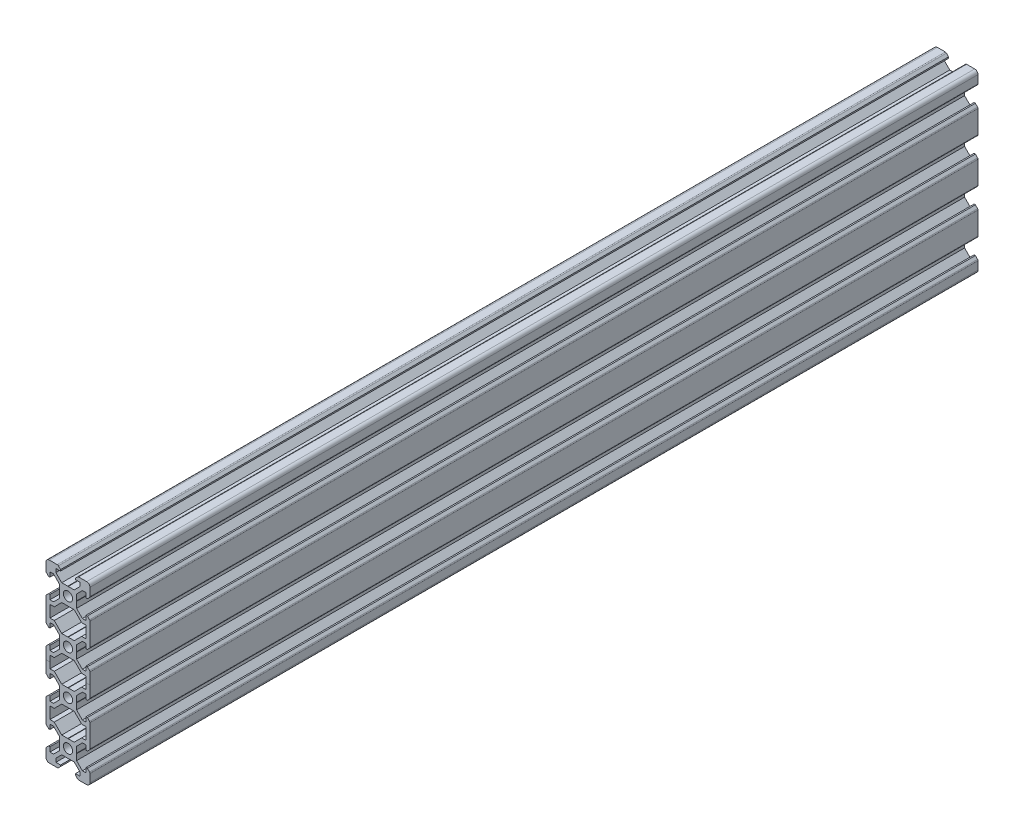
SolidWorks part; units mm, degrees
material "6063-T5"
ref_plane "Front" through (0, 0, 0) normal (0, 0, 1) x (1, 0, 0)
ref_plane "Top" through (0, 0, 0) normal (0, 1, 0) x (1, 0, 0)
ref_plane "Right" through (0, 0, 0) normal (1, 0, 0) x (0, 0, -1)
sketch "Sketch1" plane through (0, 0, 0) normal (0, 0, 1) x (1, 0, 0)
  line L0 (-8.5, 10) -> (-10, 8.5) construction
  line L1 (-8.5, 10) -> (-4.8628, 10)
  line L2 (-10, 8.5) -> (-10, 4.8628)
  line L3 (25.9287, -20) -> (-28.3599, -20) construction
  line L4 (10, 8.5) -> (10, 4.8628)
  line L5 (-10, 10) -> (10, -10) construction
  line L6 (-10, -10) -> (10, 10) construction
  line L7 (8.2, -5.5) -> (8.2, -3.3865)
  line L8 (-8.2, -5.5) -> (-8.2, -3.3865)
  line L9 (-5.5, 8.2) -> (-3.3865, 8.2)
  line L10 (-8.2, -12.7) -> (-8.2, -7.3)
  line L11 (-3.9005, 2.8395) -> (-6.561, 5.5)
  line L12 (-6.561, 5.5) -> (-8.2, 5.5)
  line L13 (-2.8395, -3.9005) -> (-0.1, -3.9005)
  line L14 (-3.9005, -2.8395) -> (-3.9005, -0.1)
  line L15 (-2.8395, 3.9005) -> (-0.1, 3.9005)
  line L16 (3.9005, -2.8395) -> (3.9005, -0.1)
  line L17 (-8.2, 3.3865) -> (-8.81, 3.3865)
  line L18 (-8.81, 3.3865) -> (-9.7976, 4.3741)
  line L19 (8.5, 10) -> (10, 8.5) construction
  line L20 (-2.8395, 3.9005) -> (-5.5, 6.561)
  line L21 (-5.5, 6.561) -> (-5.5, 8.2)
  line L22 (-3.3865, 8.2) -> (-3.3865, 8.81)
  line L23 (-3.3865, 8.81) -> (-4.3741, 9.7976)
  line L24 (0, 24.069) -> (0, -33.8154) construction
  line L25 (3.3865, 8.81) -> (4.3741, 9.7976)
  line L26 (3.3865, 8.2) -> (3.3865, 8.81)
  line L27 (5.5, 6.561) -> (5.5, 8.2)
  line L28 (2.8395, 3.9005) -> (5.5, 6.561)
  line L29 (3.3865, 8.2) -> (5.5, 8.2)
  line L30 (4.8628, 10) -> (8.5, 10)
  line L31 (-0.1, 3.9005) -> (0, 3.8005)
  line L32 (0.1, 3.9005) -> (0, 3.8005)
  line L33 (0.1, 3.9005) -> (2.8395, 3.9005)
  line L34 (25.9287, 0) -> (-28.3459, 0) construction
  line L35 (-0.1, -3.9005) -> (0, -3.8005)
  line L36 (0.1, -3.9005) -> (0, -3.8005)
  line L37 (0.1, -3.9005) -> (2.8395, -3.9005)
  line L38 (-3.9005, 0.1) -> (-3.8005, 0)
  line L39 (-3.8005, 0) -> (-3.9005, -0.1)
  line L40 (-3.9005, 0.1) -> (-3.9005, 2.8395)
  line L41 (3.9005, 0.1) -> (3.8005, 0)
  line L42 (3.8005, 0) -> (3.9005, -0.1)
  line L43 (3.9005, 0.1) -> (3.9005, 2.8395)
  line L44 (8.81, 3.3865) -> (9.7976, 4.3741)
  line L45 (8.2, 3.3865) -> (8.81, 3.3865)
  line L46 (6.561, 5.5) -> (8.2, 5.5)
  line L47 (3.9005, 2.8395) -> (6.561, 5.5)
  line L48 (2.8395, -3.9005) -> (5.5, -6.561)
  line L49 (3.9005, -2.8395) -> (6.561, -5.5)
  line L50 (-2.8395, -3.9005) -> (-5.5, -6.561)
  line L51 (-3.9005, -2.8395) -> (-6.561, -5.5)
  line L52 (6.561, -5.5) -> (8.2, -5.5)
  line L53 (-6.561, -5.5) -> (-8.2, -5.5)
  line L54 (-8.81, -3.3865) -> (-9.7976, -4.3741)
  line L55 (-8.2, -3.3865) -> (-8.81, -3.3865)
  line L56 (8.81, -3.3865) -> (9.7976, -4.3741)
  line L57 (8.2, -3.3865) -> (8.81, -3.3865)
  line L58 (8.2, 3.3865) -> (8.2, 5.5)
  line L59 (10, -4.8628) -> (10, -15.1372)
  line L60 (-8.2, 3.3865) -> (-8.2, 5.5)
  line L61 (-10, -4.8628) -> (-10, -15.1372)
  line L62 (-28.3459, -10) -> (-10, -10) construction
  line L63 (-3.9005, -20.1) -> (-3.9005, -22.8395)
  line L64 (-3.9005, -20.1) -> (-3.8005, -20)
  line L65 (-3.8005, -20) -> (-3.9005, -19.9)
  line L66 (3.9005, -20.1) -> (3.9005, -22.8395)
  line L67 (3.9005, -20.1) -> (3.8005, -20)
  line L68 (3.8005, -20) -> (3.9005, -19.9)
  line L69 (6.561, -14.5) -> (8.2, -14.5)
  line L70 (3.9005, -17.1605) -> (6.561, -14.5)
  line L71 (3.9005, -17.1605) -> (3.9005, -19.9)
  line L72 (-3.9005, -17.1605) -> (-3.9005, -19.9)
  line L73 (-3.9005, -17.1605) -> (-6.561, -14.5)
  line L74 (-6.561, -14.5) -> (-8.2, -14.5)
  line L75 (-8.2, -16.6135) -> (-8.81, -16.6135)
  line L76 (-8.81, -16.6135) -> (-9.7976, -15.6259)
  line L77 (8.2, -16.6135) -> (8.81, -16.6135)
  line L78 (8.81, -16.6135) -> (9.7976, -15.6259)
  line L79 (-2.8395, -16.0995) -> (-5.5, -13.439)
  line L80 (-2.8395, -16.0995) -> (-0.1, -16.0995)
  line L81 (-0.1, -16.0995) -> (0, -16.1995)
  line L82 (0.1, -16.0995) -> (0, -16.1995)
  line L83 (0.1, -16.0995) -> (2.8395, -16.0995)
  line L84 (2.8395, -16.0995) -> (5.5, -13.439)
  line L85 (-8.2, -16.6135) -> (-8.2, -14.5)
  line L86 (8.2, -16.6135) -> (8.2, -14.5)
  line L87 (2.8395, -23.9005) -> (5.5, -26.561)
  line L88 (-2.8395, -23.9005) -> (-5.5, -26.561)
  line L89 (-0.1, -23.9005) -> (0, -23.8005)
  line L90 (0.1, -23.9005) -> (0, -23.8005)
  line L91 (0.1, -23.9005) -> (2.8395, -23.9005)
  line L92 (-2.8395, -23.9005) -> (-0.1, -23.9005)
  line L93 (-8.2, -23.3865) -> (-8.2, -25.5)
  line L94 (-8.2, -23.3865) -> (-8.81, -23.3865)
  line L95 (-8.81, -23.3865) -> (-9.7976, -24.3741)
  line L96 (8.2, -23.3865) -> (8.2, -25.5)
  line L97 (8.2, -23.3865) -> (8.81, -23.3865)
  line L98 (8.81, -23.3865) -> (9.7976, -24.3741)
  line L99 (8.2, -27.3) -> (8.2, -32.7)
  line L100 (10, -35.1372) -> (10, -24.8628)
  line L101 (-10, -35.1372) -> (-10, -24.8628)
  line L102 (-8.2, -27.3) -> (-8.2, -32.7)
  line L103 (3.9005, -22.8395) -> (6.561, -25.5)
  line L104 (-3.9005, -22.8395) -> (-6.561, -25.5)
  line L105 (6.239, -27.3) -> (8.2, -27.3)
  line L106 (-6.239, -27.3) -> (-8.2, -27.3)
  line L107 (-6.561, -25.5) -> (-8.2, -25.5)
  line L108 (6.561, -25.5) -> (8.2, -25.5)
  line L109 (5.5, -26.561) -> (6.239, -27.3)
  line L110 (-5.5, -26.561) -> (-6.239, -27.3)
  line L111 (8.2, -34.5) -> (8.2, -36.6135)
  line L112 (8.2, -36.6135) -> (8.81, -36.6135)
  line L113 (8.81, -36.6135) -> (9.7976, -35.6259)
  line L114 (-8.2, -34.5) -> (-8.2, -36.6135)
  line L115 (-6.239, -7.3) -> (-8.2, -7.3)
  line L116 (-5.5, -6.561) -> (-6.239, -7.3)
  line L117 (6.239, -7.3) -> (8.2, -7.3)
  line L118 (5.5, -6.561) -> (6.239, -7.3)
  line L119 (-6.239, -12.7) -> (-8.2, -12.7)
  line L120 (-5.5, -13.439) -> (-6.239, -12.7)
  line L121 (5.5, -13.439) -> (6.239, -12.7)
  line L122 (6.239, -12.7) -> (8.2, -12.7)
  line L123 (8.2, -12.7) -> (8.2, -7.3)
  line L124 (-8.2, -36.6135) -> (-8.81, -36.6135)
  line L125 (10, -10) -> (25.9287, -10) construction
  line L126 (-8.81, -36.6135) -> (-9.7976, -35.6259)
  line L127 (-0.1, -56.0995) -> (0, -56.1995)
  line L128 (-0.1, -36.0995) -> (0, -36.1995)
  line L129 (0.1, -36.0995) -> (0, -36.1995)
  line L130 (0.1, -36.0995) -> (2.8395, -36.0995)
  line L131 (-6.561, -34.5) -> (-8.2, -34.5)
  line L132 (6.561, -34.5) -> (8.2, -34.5)
  line L133 (6.239, -32.7) -> (8.2, -32.7)
  line L134 (-6.239, -32.7) -> (-8.2, -32.7)
  line L135 (-5.5, -33.439) -> (-6.239, -32.7)
  line L136 (5.5, -33.439) -> (6.239, -32.7)
  line L137 (-26.6965, -30) -> (27.5921, -30) construction
  line L138 (0.1, -56.0995) -> (0, -56.1995)
  line L139 (0.1, -56.0995) -> (2.8395, -56.0995)
  line L140 (-2.8395, -56.0995) -> (-0.1, -56.0995)
  line L141 (0, -60) -> (0, -71.7864) construction
  line L142 (-3.8005, -60) -> (-3.9005, -59.9)
  line L143 (-3.9005, -60.1) -> (-3.8005, -60)
  line L144 (10, -68.5) -> (10, -64.8628)
  line L145 (0.1, -63.9005) -> (0, -63.8005)
  line L146 (-0.1, -63.9005) -> (0, -63.8005)
  line L147 (-2.8395, -63.9005) -> (-0.1, -63.9005)
  line L148 (0.1, -63.9005) -> (2.8395, -63.9005)
  line L149 (3.9005, -60.1) -> (3.9005, -62.8395)
  line L150 (3.9005, -60.1) -> (3.8005, -60)
  line L151 (3.8005, -60) -> (3.9005, -59.9)
  line L152 (3.9005, -57.1605) -> (3.9005, -59.9)
  line L153 (4.8628, -70) -> (8.5, -70)
  line L154 (3.3865, -68.81) -> (4.3741, -69.7976)
  line L155 (3.3865, -68.2) -> (3.3865, -68.81)
  line L156 (3.3865, -68.2) -> (5.5, -68.2)
  line L157 (-0.1, -43.9005) -> (0, -43.8005)
  line L158 (0.1, -43.9005) -> (0, -43.8005)
  line L159 (-2.8395, -43.9005) -> (-0.1, -43.9005)
  line L160 (0.1, -43.9005) -> (2.8395, -43.9005)
  line L161 (3.9005, -40.1) -> (3.8005, -40)
  line L162 (3.8005, -40) -> (3.9005, -39.9)
  line L163 (3.9005, -37.1605) -> (3.9005, -39.9)
  line L164 (3.9005, -40.1) -> (3.9005, -42.8395)
  line L165 (-2.8395, -36.0995) -> (-0.1, -36.0995)
  line L166 (-2.8395, -43.9005) -> (-5.5, -46.561)
  line L167 (-3.9005, -37.1605) -> (-3.9005, -39.9)
  line L168 (-3.8005, -40) -> (-3.9005, -39.9)
  line L169 (-3.9005, -40.1) -> (-3.8005, -40)
  line L170 (-3.9005, -42.8395) -> (-6.561, -45.5)
  line L171 (2.8395, -43.9005) -> (5.5, -46.561)
  line L172 (3.9005, -42.8395) -> (6.561, -45.5)
  line L173 (3.9005, -37.1605) -> (6.561, -34.5)
  line L174 (2.8395, -36.0995) -> (5.5, -33.439)
  line L175 (-3.9005, -42.8395) -> (-3.9005, -40.1)
  line L176 (-6.561, -34.5) -> (-3.9005, -37.1605)
  line L177 (-5.5, -33.439) -> (-2.8395, -36.0995)
  line L178 (5.5, -66.561) -> (5.5, -68.2)
  line L179 (6.561, -65.5) -> (8.2, -65.5)
  line L180 (8.2, -63.3865) -> (8.2, -65.5)
  line L181 (8.81, -63.3865) -> (9.7976, -64.3741)
  line L182 (8.2, -63.3865) -> (8.81, -63.3865)
  line L183 (-8.2, -63.3865) -> (-8.81, -63.3865)
  line L184 (-8.81, -63.3865) -> (-9.7976, -64.3741)
  line L185 (-8.2, -63.3865) -> (-8.2, -65.5)
  line L186 (-6.561, -65.5) -> (-8.2, -65.5)
  line L187 (-5.5, -66.561) -> (-5.5, -68.2)
  line L188 (-5.5, -68.2) -> (-3.3865, -68.2)
  line L189 (-3.3865, -68.2) -> (-3.3865, -68.81)
  line L190 (-3.3865, -68.81) -> (-4.3741, -69.7976)
  line L191 (-10, -68.5) -> (-10, -64.8628)
  line L192 (-8.5, -70) -> (-4.8628, -70)
  line L193 (-8.2, -43.3865) -> (-8.81, -43.3865)
  line L194 (-8.81, -43.3865) -> (-9.7976, -44.3741)
  line L195 (-10, -55.1372) -> (-10, -44.8628)
  line L196 (-8.81, -56.6135) -> (-9.7976, -55.6259)
  line L197 (-8.2, -56.6135) -> (-8.81, -56.6135)
  line L198 (8.2, -56.6135) -> (8.81, -56.6135)
  line L199 (8.81, -56.6135) -> (9.7976, -55.6259)
  line L200 (8.2, -43.3865) -> (8.81, -43.3865)
  line L201 (8.81, -43.3865) -> (9.7976, -44.3741)
  line L202 (10, -55.1372) -> (10, -44.8628)
  line L203 (-8.2, -47.3) -> (-8.2, -52.7)
  line L204 (8.2, -47.3) -> (8.2, -52.7)
  line L205 (-6.239, -52.7) -> (-8.2, -52.7)
  line L206 (6.239, -52.7) -> (8.2, -52.7)
  line L207 (-6.561, -54.5) -> (-8.2, -54.5)
  line L208 (6.561, -54.5) -> (8.2, -54.5)
  line L209 (-3.9005, -60.1) -> (-3.9005, -62.8395)
  line L210 (-2.8395, -56.0995) -> (-5.5, -53.439)
  line L211 (3.9005, -57.1605) -> (6.561, -54.5)
  line L212 (2.8395, -56.0995) -> (5.5, -53.439)
  line L213 (5.5, -53.439) -> (6.239, -52.7)
  line L214 (-5.5, -53.439) -> (-6.239, -52.7)
  line L215 (-8.2, -43.3865) -> (-8.2, -45.5)
  line L216 (8.2, -43.3865) -> (8.2, -45.5)
  line L217 (-2.8395, -63.9005) -> (-5.5, -66.561)
  line L218 (-3.9005, -62.8395) -> (-6.561, -65.5)
  line L219 (2.8395, -63.9005) -> (5.5, -66.561)
  line L220 (3.9005, -62.8395) -> (6.561, -65.5)
  line L221 (-8.2, -54.5) -> (-8.2, -56.6135)
  line L222 (8.2, -54.5) -> (8.2, -56.6135)
  line L223 (6.239, -47.3) -> (8.2, -47.3)
  line L224 (-6.239, -47.3) -> (-8.2, -47.3)
  line L225 (-6.561, -45.5) -> (-8.2, -45.5)
  line L226 (-5.5, -46.561) -> (-6.239, -47.3)
  line L227 (6.561, -45.5) -> (8.2, -45.5)
  line L228 (5.5, -46.561) -> (6.239, -47.3)
  line L229 (-3.9005, -57.1605) -> (-3.9005, -59.9)
  line L230 (-3.9005, -57.1605) -> (-6.561, -54.5)
  circle A0 centre (0, 0) radius 2.1
  arc A1 (-8.5, 10) -> (-10, 8.5) centre (-8.5, 8.5) ccw
  arc A2 (10, 8.5) -> (8.5, 10) centre (8.5, 8.5) ccw
  arc A3 (-4.3741, 9.7976) -> (-4.8628, 10) centre (-4.8628, 9.3088) ccw
  arc A4 (4.8628, 10) -> (4.3741, 9.7976) centre (4.8628, 9.3088) ccw
  circle A5 centre (0, -20) radius 2.1
  arc A6 (9.7976, 4.3741) -> (10, 4.8628) centre (9.3088, 4.8628) ccw
  arc A7 (-10, 4.8628) -> (-9.7976, 4.3741) centre (-9.3088, 4.8628) ccw
  arc A8 (-10, -4.8628) -> (-9.7976, -4.3741) centre (-9.3088, -4.8628) cw
  arc A9 (9.7976, -4.3741) -> (10, -4.8628) centre (9.3088, -4.8628) cw
  arc A10 (-10, -15.1372) -> (-9.7976, -15.6259) centre (-9.3088, -15.1372) ccw
  arc A11 (9.7976, -15.6259) -> (10, -15.1372) centre (9.3088, -15.1372) ccw
  arc A12 (-10, -24.8628) -> (-9.7976, -24.3741) centre (-9.3088, -24.8628) cw
  arc A13 (9.7976, -24.3741) -> (10, -24.8628) centre (9.3088, -24.8628) cw
  arc A14 (9.7976, -35.6259) -> (10, -35.1372) centre (9.3088, -35.1372) ccw
  arc A15 (-10, -35.1372) -> (-9.7976, -35.6259) centre (-9.3088, -35.1372) ccw
  circle A16 centre (0, -40) radius 2.1
  circle A17 centre (0, -60) radius 2.1
  arc A18 (10, -68.5) -> (8.5, -70) centre (8.5, -68.5) cw
  arc A19 (4.8628, -70) -> (4.3741, -69.7976) centre (4.8628, -69.3088) cw
  arc A20 (9.7976, -64.3741) -> (10, -64.8628) centre (9.3088, -64.8628) cw
  arc A21 (-10, -64.8628) -> (-9.7976, -64.3741) centre (-9.3088, -64.8628) cw
  arc A22 (-4.3741, -69.7976) -> (-4.8628, -70) centre (-4.8628, -69.3088) cw
  arc A23 (-8.5, -70) -> (-10, -68.5) centre (-8.5, -68.5) cw
  arc A24 (-10, -44.8628) -> (-9.7976, -44.3741) centre (-9.3088, -44.8628) cw
  arc A25 (-10, -55.1372) -> (-9.7976, -55.6259) centre (-9.3088, -55.1372) ccw
  arc A26 (9.7976, -55.6259) -> (10, -55.1372) centre (9.3088, -55.1372) ccw
  arc A27 (9.7976, -44.3741) -> (10, -44.8628) centre (9.3088, -44.8628) cw
  point P17 (-9.25, 9.25)
  point P21 (9.25, 9.25)
  point P181 (-10, -30)
  dimension "D2" = 4.2
  dimension "D4" = 1.5
  dimension "D3" = 20
  dimension "D5" = 0.529
  dimension "D6" = 6.773
  dimension "D7" = 90
  dimension "D8" = 11
  dimension "D9" = 0.61
  dimension "D10" = 0.1
  dimension "D11" = 0.1
  dimension "D12" = 0.1
  dimension "D13" = 0.1
  dimension "D14" = 5.679
  dimension "D15" = 1.639
  dimension "D16" = 1.8
  dimension "D17" = 90
  dimension "D18" = 6.773
  dimension "D19" = 90
  dimension "D20" = 20
  dimension "D21" = 1.8
extrude "Boss-Extrude2" add sketch "Sketch1" along normal blind 404
sketch "Sketch2" plane through (0, 0, 404) normal (0, 0, 1) x (1, 0, 0)
  line L0 (-10, -30) -> (10, -30)
  line L1 (-10, -24.8628) -> (-10, -35.1372) construction
  line L2 (10, -35.1372) -> (10, -24.8628) construction
split line "SideFixture1 - SplitLine"
sketch "Sketch3" plane through (0, 0, 0) normal (0, 0, -1) x (-1, 0, 0)
  line L0 (-10, -30) -> (10, -30)
  line L1 (-10, -35.1372) -> (-10, -24.8628) construction
  line L2 (10, -24.8628) -> (10, -35.1372) construction
split line "SideFixture2 - SplitLine"
sketch "Sketch4" plane through (0, 10, 0) normal (0, 1, 0) x (1, 0, 0)
  line L0 (8.5, -202) -> (-8.5, -202)
  line L1 (8.5, -404) -> (8.5, 0) construction
  line L2 (-8.5, -404) -> (-8.5, 0) construction
split line "SideFixture3 - SplitLine"
equation "\"base-xwidth\"= 455mm"
equation "\"base-yheight\"= 533mm"
equation "\"base-zdepth\"= 377mm"
equation "\"D1@Boss-Extrude2\"=\"base-xwidth\"-51mm"
